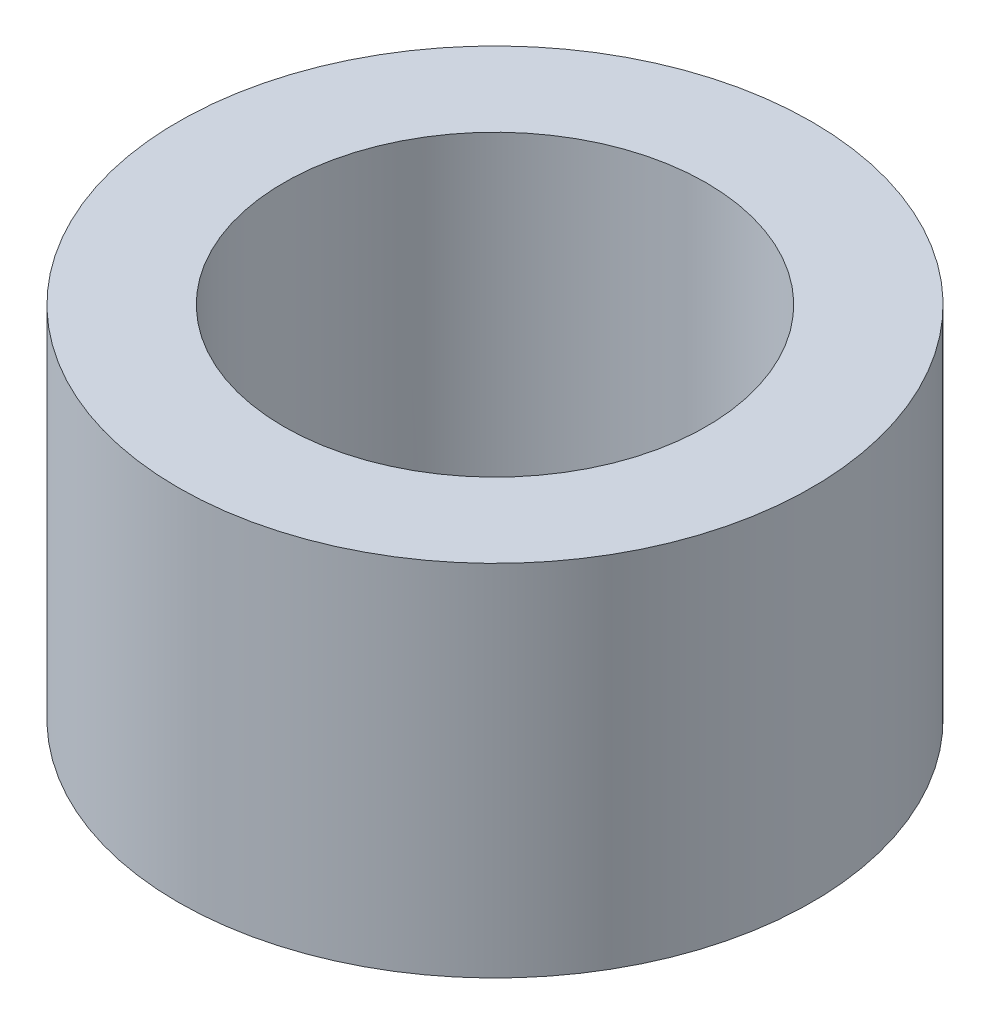
SolidWorks part; units mm, degrees
ref_plane "Front Plane" through (0, 0, 0) normal (0, 0, 1) x (1, 0, 0)
ref_plane "Top Plane" through (0, 0, 0) normal (0, 1, 0) x (1, 0, 0)
ref_plane "Right Plane" through (0, 0, 0) normal (1, 0, 0) x (0, 0, -1)
sketch "Sketch1" plane through (0, 0, 0) normal (0, 1, 0) x (1, 0, 0)
  circle A0 centre (0, 0) radius 10
  circle A1 centre (0, 0) radius 15
  dimension "D1" = 20
  dimension "D2" = 30
extrude "Boss-Extrude1" add sketch "Sketch1" along normal blind 17
sketch "Sketch2" plane through (0, 0, 0) normal (0, -1, 0) x (1, 0, 0)
  circle A0 centre (0, 0) radius 10.95
  circle A1 centre (0, 0) radius 10
  dimension "D1" = 21.9
extrude "Boss-Extrude2" add sketch "Sketch2" along normal blind 2.5
